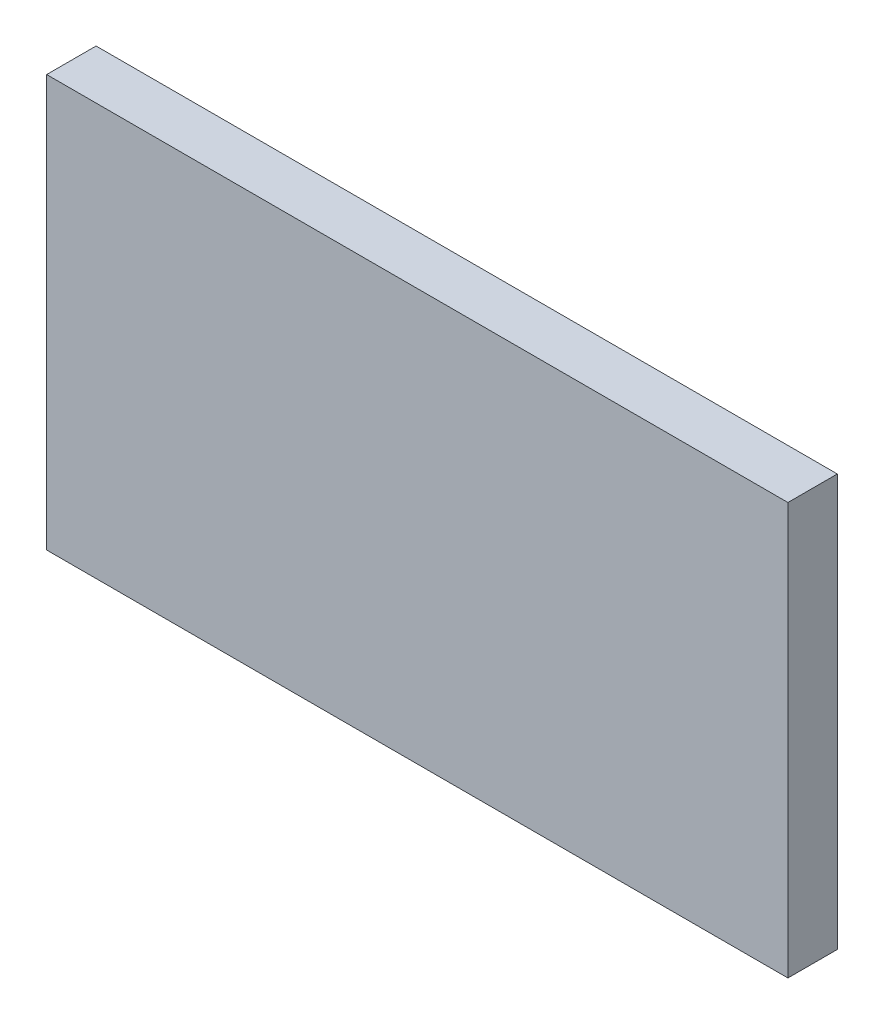
SolidWorks part; units mm, degrees
ref_plane "Front Plane" through (0, 0, 0) normal (0, 0, 1) x (1, 0, 0)
ref_plane "Top Plane" through (0, 0, 0) normal (0, 1, 0) x (1, 0, 0)
ref_plane "Right Plane" through (0, 0, 0) normal (1, 0, 0) x (0, 0, -1)
sketch "Sketch1" plane through (0, 0, 0) normal (0, 0, 1) x (1, 0, 0)
  line L1 (-21.0264, 12.9293) -> (23.9736, 12.9293)
  line L2 (-21.0264, 12.9293) -> (-21.0264, -12.0707)
  line L3 (-21.0264, -12.0707) -> (23.9736, -12.0707)
  line L4 (23.9736, 12.9293) -> (23.9736, -12.0707)
extrude "Boss-Extrude1" add sketch "Sketch1" along normal blind 3
